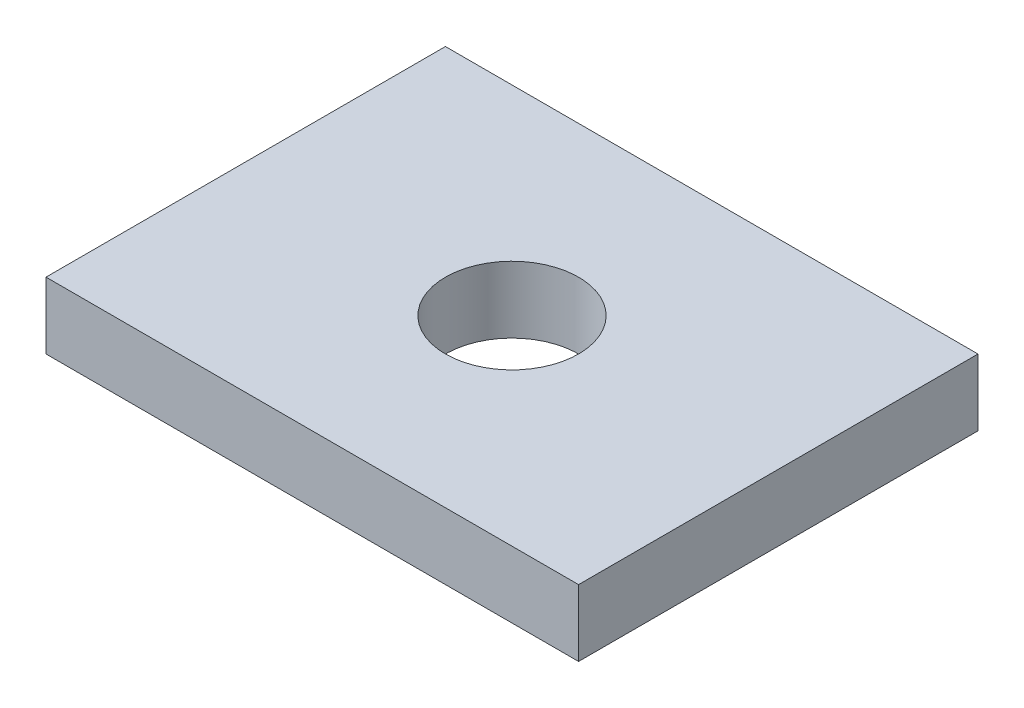
SolidWorks part; units mm, degrees
ref_plane "Front Plane" through (0, 0, 0) normal (0, 0, 1) x (1, 0, 0)
ref_plane "Top Plane" through (0, 0, 0) normal (0, 1, 0) x (1, 0, 0)
ref_plane "Right Plane" through (0, 0, 0) normal (1, 0, 0) x (0, 0, -1)
sketch "Sketch1" plane through (0, 0, 0) normal (0, 1, 0) x (1, 0, 0)
  line L1 (-40, 30) -> (40, 30)
  line L2 (-40, 30) -> (-40, -30)
  line L3 (-40, -30) -> (40, -30)
  line L4 (40, 30) -> (40, -30)
  line L5 (-40, 30) -> (40, -30) construction
  line L6 (-40, -30) -> (40, 30) construction
  circle A0 centre (0, 0) radius 10
  point P0 (0, 0)
  dimension "D3" = 20
  dimension "D1" = 60
  dimension "D2" = 80
extrude "Boss-Extrude1" add sketch "Sketch1" along normal blind 10
